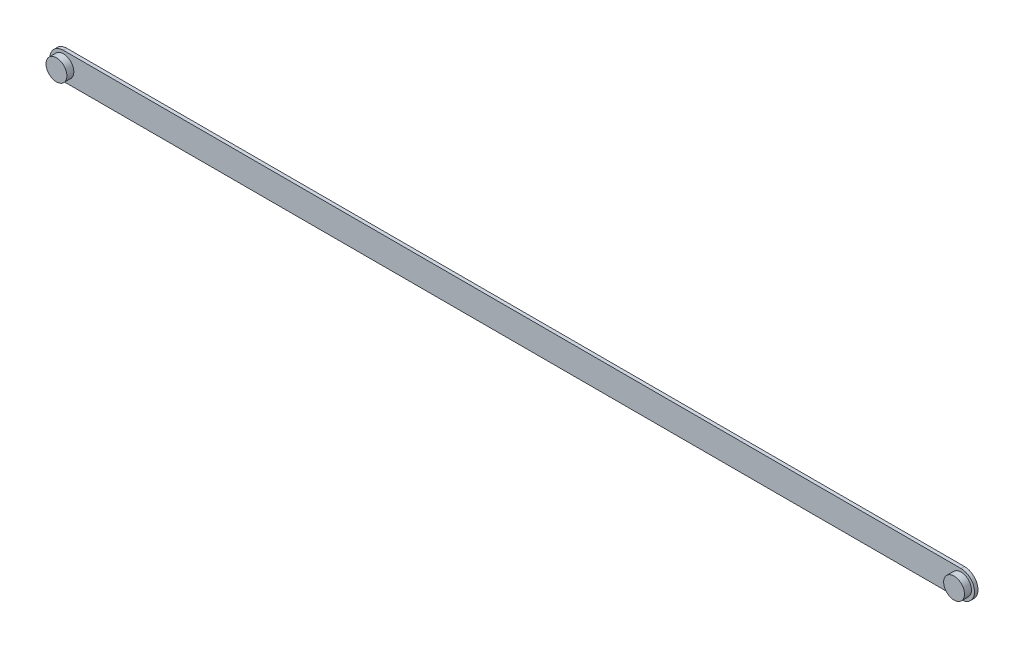
SolidWorks part; units mm, degrees
ref_plane "前视基准面" through (0, 0, 0) normal (0, 0, 1) x (1, 0, 0)
ref_plane "上视基准面" through (0, 0, 0) normal (0, 1, 0) x (1, 0, 0)
ref_plane "右视基准面" through (0, 0, 0) normal (1, 0, 0) x (0, 0, -1)
other "Configuration Table"
sketch "草图1" plane through (0, 0, 0) normal (0, 0, 1) x (1, 0, 0)
  line L0 (0, 0) -> (-258.0533, 0) construction
  line L1 (0, -3.8748) -> (-258.0533, -3.8748)
  line L2 (0, 3.8748) -> (-258.0533, 3.8748)
  arc A0 (0, -3.8748) -> (0, 3.8748) centre (0, 0) ccw
  arc A1 (-258.0533, 3.8748) -> (-258.0533, -3.8748) centre (-258.0533, 0) ccw
  point P3 (-129.0266, 0)
  point P9 (-258.0533, -1.3483)
extrude "凸台-拉伸1" add sketch "草图1" along normal blind 1
sketch "草图2" plane through (0, 0, 1) normal (0, 0, 1) x (1, 0, 0)
  circle A0 centre (0, 0) radius 3
  dimension "D1" = 6
extrude "凸台-拉伸2" add sketch "草图2" along normal blind 2
sketch "草图3" plane through (0, 0, 1) normal (0, 0, 1) x (1, 0, 0)
  circle A0 centre (-258.0533, 0) radius 3
  dimension "D1" = 6
extrude "凸台-拉伸3" add sketch "草图3" along normal blind 2
